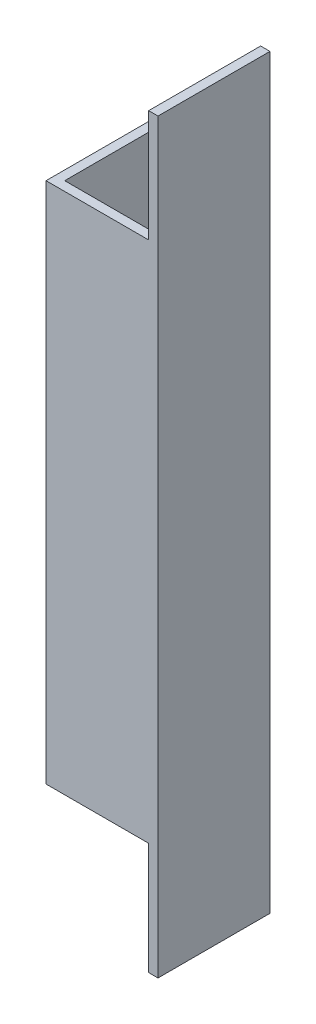
SolidWorks part; units mm, degrees
ref_plane "Front Plane" through (0, 0, 0) normal (0, 0, 1) x (1, 0, 0)
ref_plane "Top Plane" through (0, 0, 0) normal (0, 1, 0) x (1, 0, 0)
ref_plane "Right Plane" through (0, 0, 0) normal (1, 0, 0) x (0, 0, -1)
sketch "Sketch1" plane through (0, 0, 0) normal (0, 1, 0) x (1, 0, 0)
  line L1 (0, 0) -> (19.05, 0)
  line L2 (0, 0) -> (0, 19.05)
  line L3 (0, 19.05) -> (19.05, 19.05)
  line L4 (19.05, 0) -> (19.05, 19.05)
  dimension "D1" = 19.05
  dimension "D2" = 19.05
extrude "Extrude-Thin1" add sketch "Sketch1" along normal blind 127 thin thin type one direction reverse wall 1.5875
sketch "Sketch2" plane through (0, 0, 0) normal (-1, 0, 0) x (0, 0, 1)
  line L0 (-19.05, 127) -> (-19.05, 0) construction
  line L1 (0, 0) -> (-19.05, 0)
  line L2 (0, 0) -> (0, 19.05)
  line L3 (0, 19.05) -> (-19.05, 19.05)
  line L4 (-19.05, 0) -> (-19.05, 19.05)
  dimension "D1" = 19.05
extrude "Cut-Extrude1" cut sketch "Sketch2" against normal blind 17.4625
sketch "Sketch3" plane through (0, 0, 0) normal (-1, 0, 0) x (0, 0, 1)
  line L0 (-19.05, 127) -> (-19.05, 19.05) construction
  line L1 (0, 127) -> (-19.05, 127)
  line L2 (0, 127) -> (0, 107.95)
  line L3 (0, 107.95) -> (-19.05, 107.95)
  line L4 (-19.05, 127) -> (-19.05, 107.95)
  dimension "D1" = 19.05
extrude "Cut-Extrude2" cut sketch "Sketch3" against normal blind 17.4625
